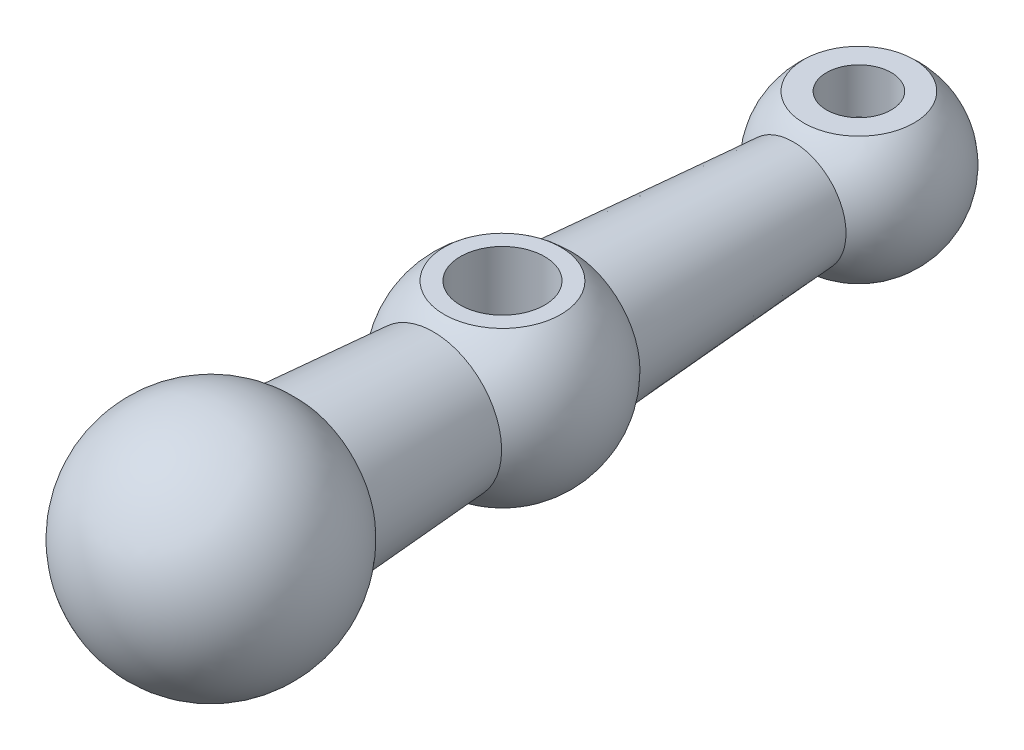
SolidWorks part; units mm, degrees
material "Stainless Steel (ferritic)"
ref_plane "Front Plane" through (0, 0, 0) normal (0, 0, 1) x (1, 0, 0)
ref_plane "Top Plane" through (0, 0, 0) normal (0, 1, 0) x (1, 0, 0)
ref_plane "Right Plane" through (0, 0, 0) normal (1, 0, 0) x (0, 0, -1)
sketch "Sketch1" plane through (0, 0, 0) normal (1, 0, 0) x (0, 0, -1)
  line L0 (-63, 0) -> (68, 0)
  line L1 (-31.5836, 12) -> (-10.6748, 10.5379)
  line L2 (10.6748, 10.5379) -> (44.8694, 8.1468)
  line L3 (-31.5836, 12) -> (-3.3737, 12) construction
  line L4 (10.6748, 10.5379) -> (25.5561, 10.5379) construction
  arc A0 (10.6748, 10.5379) -> (-10.6748, 10.5379) centre (0, 0) ccw
  arc A2 (68, 0) -> (44.8694, 8.1468) centre (55, 0) ccw
  arc A3 (-31.5836, 12) -> (-63, 0) centre (-45, 0) ccw
  dimension "D1" = 26
  dimension "R1" = 36
  dimension "D2" = 30
  dimension "D3" = 12
  dimension "D4" = 45
  dimension "D5" = 100
  dimension "D6" = 4
  dimension "D7" = 4
revolve "Revolve1" add sketch "Sketch1" angle 360 about L0
sketch "Sketch2" plane through (0, 0, 0) normal (0, 1, 0) x (1, 0, 0)
  circle A0 centre (0, 0) radius 6.5
  dimension "D1" = 13
extrude "Cut-Extrude1" cut sketch "Sketch2" against normal through all both and the other way through all
sketch "Sketch5" plane through (0, 0, 0) normal (0, 1, 0) x (1, 0, 0)
  circle A0 centre (0, 0) radius 9
  circle A1 centre (0, 0) radius 6.5
  circle A2 centre (0, 0) radius 6.5 construction
  dimension "D1" = 18
sketch "Sketch6" plane through (0, 0, 0) normal (1, 0, 0) x (0, 0, -1)
  line L0 (-9, 12) -> (9, 12)
  line L1 (-9, -12) -> (9, -12)
  line L2 (46.5, 9.8362) -> (63.5, 9.8362)
  line L3 (-6.5, -13.5185) -> (6.5, -13.5185) construction
  line L4 (6.5, 13.5185) -> (-6.5, 13.5185) construction
  line L5 (-6.5, -13.5185) -> (6.5, -13.5185)
  line L6 (6.5, 13.5185) -> (-6.5, 13.5185)
  arc A0 (-6.5, 13.5185) -> (-10.6748, 10.5379) centre (0, 0) ccw construction
  arc A1 (10.6748, 10.5379) -> (6.5, 13.5185) centre (0, 0) ccw construction
  arc A2 (-10.6748, -10.5379) -> (-6.5, -13.5185) centre (0, 0) ccw construction
  arc A3 (44.8694, -8.1468) -> (44.8694, 8.1468) centre (55, 0) ccw construction
  arc A4 (6.5, -13.5185) -> (10.6748, -10.5379) centre (0, 0) ccw construction
  arc A5 (63.5, 9.8362) -> (46.5, 9.8362) centre (55, 0) ccw
  arc A6 (-9, -12) -> (-6.5, -13.5185) centre (0, 0) ccw
  arc A7 (6.5, -13.5185) -> (10.6748, -10.5379) centre (0, 0) ccw
  arc A8 (9, 12) -> (6.5, 13.5185) centre (0, 0) ccw
  arc A9 (-6.5, 13.5185) -> (-9, 12) centre (0, 0) ccw
  dimension "D1" = 18
  dimension "D2" = 18
  dimension "D3" = 24
  dimension "D4" = 17
extrude "Cut-Extrude7" cut sketch "Sketch6" against normal blind 12 and the other way through all contours L6 A9 L0 A8 | L5 A7 L1 A6 | L2 A5
hole_wizard "Ø10.0mm Dowel Hole1" positions "3DSketch4" profile "Sketch9" hole size "Ø10.0" standard "ISO"
sketch3d "3DSketch4"
  circle A1 centre (0, 9.8362, -55) radius 8.5 construction
  point P0 (0.2022, 8.9535, -54.266)
  point P2 (0.2022, 8.9535, -54.266)
  point P4 (0, 9.8362, -55)
  point P14 (0, 18.3362, -55)
  dimension "D2" = 55
sketch "Sketch9" plane through (0, 9.8362, -55) normal (1, 0, 0) x (0, 0, 1)
  line L0 (0, 0) -> (0, 10)
  line L1 (0, 10) -> (5, 6.9957)
  line L2 (5, 6.9957) -> (5, 0)
  line L5 (5, 0) -> (0, 0)
  line L10 (0, 10) -> (-5, 6.9957) construction
  line L11 (0, -6.35) -> (0, 107.95) construction
  dimension "Hole Dia." = 10
  dimension "Hole Depth" = 10
  dimension "Drill Angle" = 118
